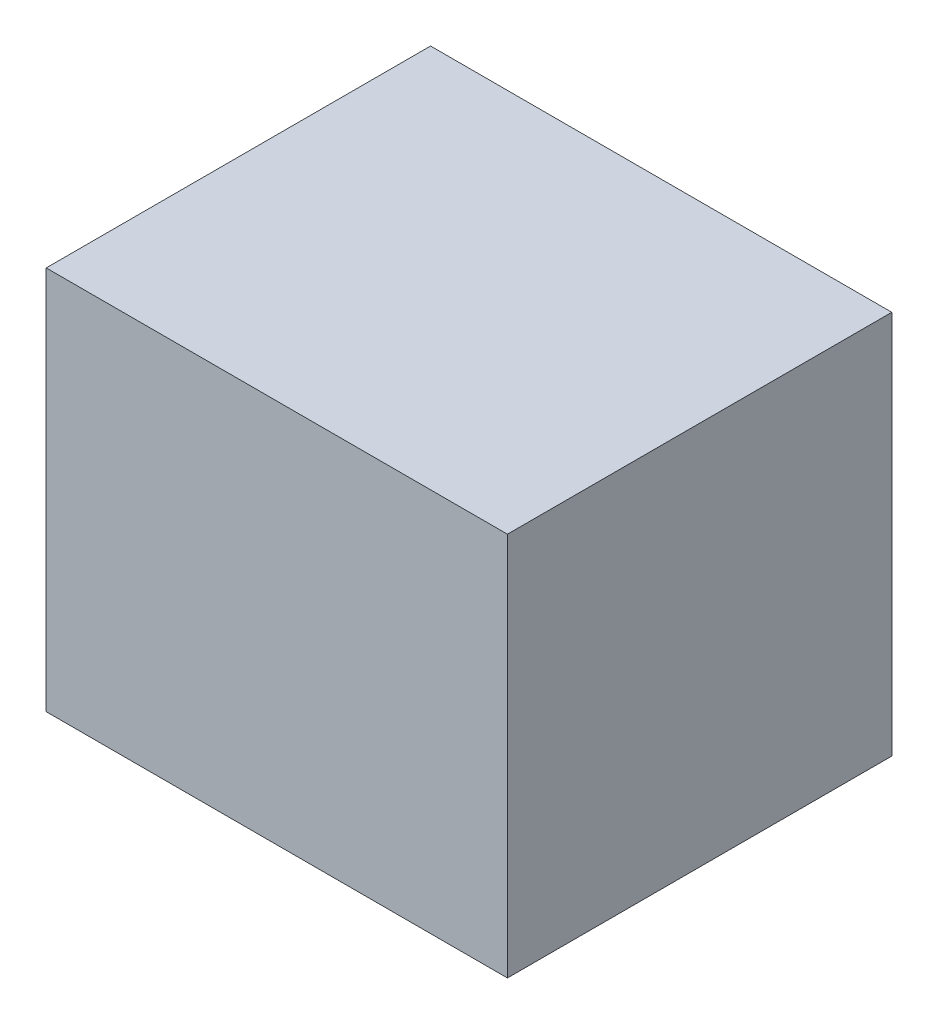
SolidWorks part; units mm, degrees
material "6061-T6 (SS)"
ref_plane "Front Plane" through (0, 0, 0) normal (0, 0, 1) x (1, 0, 0)
ref_plane "Top Plane" through (0, 0, 0) normal (0, 1, 0) x (1, 0, 0)
ref_plane "Right Plane" through (0, 0, 0) normal (1, 0, 0) x (0, 0, -1)
sketch "Sketch1" plane through (0, 0, 0) normal (0, 0, 1) x (1, 0, 0)
  line L1 (0, 0) -> (600, 0)
  line L2 (0, 0) -> (0, 500)
  line L3 (0, 500) -> (600, 500)
  line L4 (600, 0) -> (600, 500)
  dimension "Length" = 600
  dimension "Width" = 500
extrude "Boss-Extrude1" add sketch "Sketch1" along normal blind 500
shell "Shell1" thickness 35
